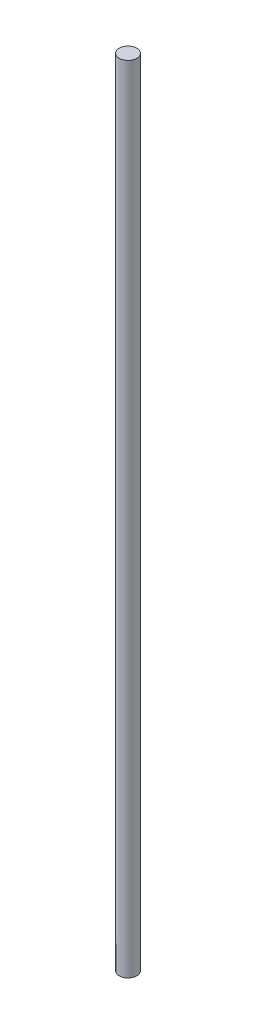
SolidWorks part; units mm, degrees
ref_plane "Alzado" through (0, 0, 0) normal (0, 0, 1) x (1, 0, 0)
ref_plane "Planta" through (0, 0, 0) normal (0, 1, 0) x (1, 0, 0)
ref_plane "Vista lateral" through (0, 0, 0) normal (1, 0, 0) x (0, 0, -1)
sketch "Croquis1" plane through (-499.6537, -70.0014, -607.7464) normal (0, 1, 0) x (-0.9835, 0, 0.1808)
  circle A0 centre (0, 0) radius 1.5
  dimension "D1" = 3
extrude "Saliente-Extruir1" add sketch "Croquis1" along normal blind 135
